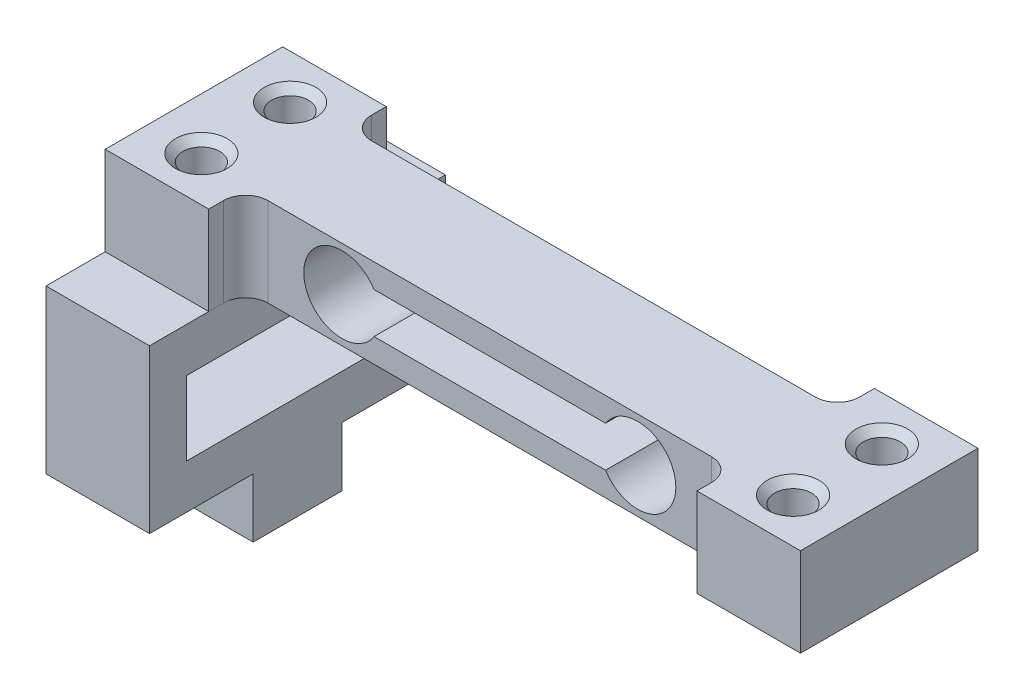
SolidWorks part; units mm, degrees
ref_plane "Front Plane" through (0, 0, 0) normal (0, 0, 1) x (1, 0, 0)
ref_plane "Top Plane" through (0, 0, 0) normal (0, 1, 0) x (1, 0, 0)
ref_plane "Right Plane" through (0, 0, 0) normal (1, 0, 0) x (0, 0, -1)
sketch "Sketch1" plane through (0, 0, 0) normal (0, 1, 0) x (1, 0, 0)
  line L0 (0, -3.5) -> (0, 3.5)
  line L1 (0, 3.5) -> (15, 3.5)
  line L2 (16.5, 5) -> (16.5, 6)
  line L3 (16.5, 6) -> (23.5, 6)
  line L4 (23.5, 6) -> (23.5, -6)
  line L5 (23.5, -6) -> (16.5, -6)
  line L6 (16.5, -5) -> (16.5, -6)
  line L7 (15, -3.5) -> (0, -3.5)
  line L8 (0, 0) -> (0, 50000) construction
  line L9 (0, 0) -> (50000, 0) construction
  arc A0 (15, 3.5) -> (16.5, 5) centre (15, 5) ccw
  arc A1 (16.5, -5) -> (15, -3.5) centre (15, -5) ccw
  point P4 (0, 0)
  dimension "D1" = 12
  dimension "D4" = 1.5
  dimension "D2" = 47
  dimension "D3" = 7
  dimension "D5" = 7
extrude "Boss-Extrude1" add sketch "Sketch1" along normal mid plane 6
sketch "Sketch2" plane through (0, 0, 3.5) normal (0, 0, 1) x (1, 0, 0)
  line L0 (0, 3) -> (0, -3) construction
  line L1 (-10, -1.375) -> (10, -1.375)
  line L2 (-10, -1.375) -> (-10, 1.375)
  line L3 (-10, 1.375) -> (10, 1.375)
  line L4 (10, -1.375) -> (10, 1.375)
  line L5 (-10, -1.375) -> (10, 1.375) construction
  line L6 (-10, 1.375) -> (10, -1.375) construction
  circle A0 centre (10, 0) radius 2.575
  point P0 (0, 0)
  line M6 (0, 3) -> (0, -3)
  dimension "D1" = 5.15
  dimension "D2" = 20
  dimension "D3" = 2.75
extrude "Cut-Extrude1" cut sketch "Sketch2" against normal through all contours L1 A0 L3 L4 | L3 A0 L1 L4 | A0 L3 L1 M6
sketch "Sketch3" plane through (0, 3, 0) normal (0, 1, 0) x (1, 0, 0)
  line L0 (0, 3.5) -> (0, -3.5) construction
  line L1 (-20, 3) -> (20, 3) construction
  line L2 (-20, 3) -> (-20, -3) construction
  line L3 (-20, -3) -> (20, -3) construction
  line L4 (20, 3) -> (20, -3) construction
  line L5 (-20, 3) -> (20, -3) construction
  line L6 (-20, -3) -> (20, 3) construction
  point P0 (0, 0)
  dimension "D1" = 40
  dimension "D2" = 6
hole_wizard "M3 Tapped Hole1" positions "Sketch4" profile "Sketch5" tap size "M3" standard "DIN" end condition through all
sketch "Sketch4" plane through (0, 3, 0) normal (0, 1, 0) x (1, 0, 0)
  point P0 (20, 3)
  point P3 (20, -3)
cosmetic thread "Hole Thread1" parameters "D2"=3
cosmetic thread "Hole Thread2" parameters "D2"=3
sketch "Sketch5" plane through (20, 3, -3) normal (1, 0, 0) x (0, 0, 1)
  line L0 (0, 0) -> (0, 6)
  line L1 (0, 6) -> (1.75, 6)
  line L2 (1.25, 5.5) -> (1.25, 0.5)
  line L3 (1.25, 0.5) -> (1.75, 0)
  line L5 (1.75, 0) -> (0, 0)
  line L6 (-1.25, 0.5) -> (-1.75, 0) construction
  line L7 (1.75, 6) -> (1.25, 5.5)
  line L8 (-1.75, 6) -> (-1.25, 5.5) construction
  line L11 (0, -6.35) -> (0, 107.95) construction
  dimension "Thru Tap Drill Dia." = 2.5
  dimension "Thru Tap Drill Depth" = 6
  dimension "Near C'Sink Dia." = 3.5
  dimension "Near C'Sink Angle" = 90
  dimension "Far C'Sink Dia." = 3.5
  dimension "Far C'Sink Angle" = 90
mirror "Mirror1" about plane through (0, 0, 0) normal (1, 0, 0) of bodies 103
sketch "Sketch8" plane through (0, -3, 0) normal (0, -1, 0) x (1, 0, 0)
  line L0 (-23.5, 6) -> (-23.5, -6) construction
  line L1 (-23.5, 10) -> (-16.5, 10)
  line L2 (-23.5, 10) -> (-23.5, -10)
  line L3 (-23.5, -10) -> (-16.5, -10)
  line L4 (-16.5, 10) -> (-16.5, -10)
  circle A0 centre (-20, 3) radius 1.25 construction
  circle A1 centre (-20, -3) radius 1.75 construction
  circle A2 centre (-20, 3) radius 1.75 construction
  circle A3 centre (-20, -3) radius 1.75
  circle A4 centre (-20, 3) radius 1.75
  point P6 (-23.5, 0)
  point P7 (-23.5, 0)
  dimension "D1" = 7
extrude "Boss-Extrude3" add sketch "Sketch8" along normal blind 3 separate body
sketch "Sketch9" plane through (0, -6, 0) normal (0, -1, 0) x (1, 0, 0)
  line L0 (-16.5, -10) -> (-16.5, 10) construction
  line L1 (-23.5, 10) -> (-16.5, 10)
  line L2 (-23.5, 10) -> (-23.5, 7.5)
  line L3 (-23.5, 7.5) -> (-16.5, 7.5)
  line L4 (-16.5, 10) -> (-16.5, 7.5)
  line L5 (-23.5, 0) -> (-16.5, 0) construction
  line L6 (-23.5, 10) -> (-23.5, -10) construction
  line L7 (-23.5, -7.5) -> (-16.5, -7.5)
  line L8 (-16.5, -10) -> (-16.5, -7.5)
  line L9 (-23.5, -10) -> (-16.5, -10)
  line L10 (-23.5, -10) -> (-23.5, -7.5)
  dimension "D1" = 2.5
extrude "Boss-Extrude4" add sketch "Sketch9" along normal blind 5
sketch "Sketch10" plane through (0, -11, 0) normal (0, -1, 0) x (1, 0, 0)
  line L1 (-23.5, 10) -> (-16.5, 10)
  line L2 (-23.5, 10) -> (-23.5, -10)
  line L3 (-23.5, -10) -> (-16.5, -10)
  line L4 (-16.5, 10) -> (-16.5, -10)
extrude "Boss-Extrude5" add sketch "Sketch10" along normal blind 3
sketch "Sketch11" plane through (0, -14, 0) normal (0, -1, 0) x (1, 0, 0)
  line L0 (-23.5, 10) -> (-23.5, -10) construction
  line L1 (-23.5, 3) -> (-16.5, 3)
  line L2 (-23.5, 3) -> (-23.5, -3)
  line L3 (-23.5, -3) -> (-16.5, -3)
  line L4 (-16.5, 3) -> (-16.5, -3)
  line L5 (-16.5, -10) -> (-16.5, 10) construction
  line L7 (-21.25, 1.25) -> (-18.75, 1.25)
  line L8 (-21.25, 1.25) -> (-21.25, -1.25)
  line L9 (-21.25, -1.25) -> (-18.75, -1.25)
  line L10 (-18.75, 1.25) -> (-18.75, -1.25)
  point P8 (-23.5, 0)
  point P9 (-23.5, 0)
  point P14 (-21.25, 0)
  point P15 (-20, 1.25)
  point P16 (-20, 3)
  dimension "D1" = 6
  dimension "D2" = 2.5
  dimension "D3" = 2.5
extrude "Boss-Extrude6" add sketch "Sketch11" along normal blind 4
